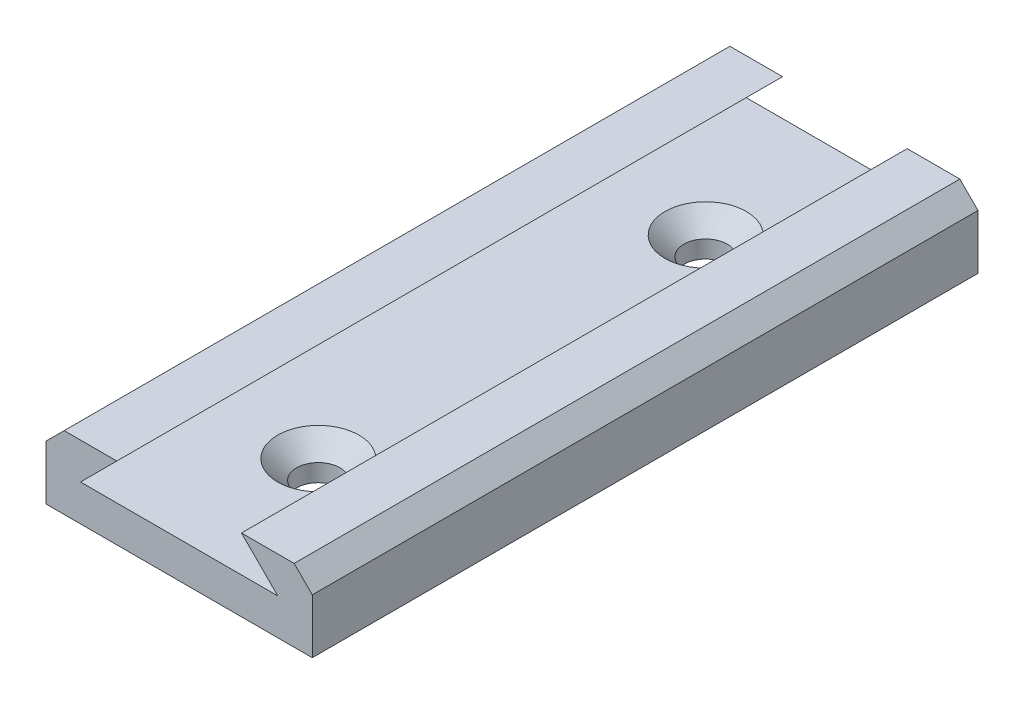
SolidWorks part; units mm, degrees
ref_plane "Front Plane" through (0, 0, 0) normal (0, 0, 1) x (1, 0, 0)
ref_plane "Top Plane" through (0, 0, 0) normal (0, 1, 0) x (1, 0, 0)
ref_plane "Right Plane" through (0, 0, 0) normal (1, 0, 0) x (0, 0, -1)
sketch "Sketch2" plane through (0, 0, 0) normal (0, 0, 1) x (1, 0, 0)
  line L0 (-11, 0) -> (11, 0)
  line L1 (11, 0) -> (11, 4.5)
  line L2 (11, 4.5) -> (9.5, 6)
  line L3 (9.5, 6) -> (5.15, 6)
  line L4 (5.15, 6) -> (8.15, 3)
  line L5 (8.15, 3) -> (-8.15, 3)
  line L6 (-8.15, 3) -> (-5.15, 6)
  line L7 (-5.15, 6) -> (-9.5, 6)
  line L8 (-9.5, 6) -> (-11, 4.5)
  line L9 (-11, 4.5) -> (-11, 0)
  point P0 (0, 0)
  point P12 (0, 3)
  dimension "D1" = 16.3
  dimension "D2" = 45
  dimension "D3" = 3
  dimension "D4" = 45
  dimension "D5" = 22
  dimension "D6" = 1.5
  dimension "D7" = 1.5
  dimension "D8" = 3
extrude "Boss-Extrude1" add sketch "Sketch2" along normal blind 55
sketch "Sketch5" plane through (0, 3, 0) normal (0, 1, 0) x (1, 0, 0)
  line L0 (-11, -27.5) -> (11, -27.5) construction
  line L1 (-11, -55) -> (-11, 0) construction
  line L2 (11, -55) -> (11, 0) construction
  point P0 (0, -11.5)
  point P2 (0, -43.5)
  point P13 (0, 0)
  dimension "D1" = 32
hole_wizard "CSK for M3 Hex Socket Countersunk Cap Screw1" positions "Sketch5" profile "Sketch4" countersink size "M3" standard "ISO" end condition through all
sketch "Sketch4" plane through (0, 3, 11.5) normal (1, 0, 0) x (0, 0, 1)
  line L0 (0, 0) -> (0, 3)
  line L1 (0, 3) -> (1.8, 3)
  line L2 (1.8, 3) -> (1.8, 1.56)
  line L3 (1.8, 1.56) -> (3.36, 0)
  line L5 (3.36, 0) -> (0, 0)
  line L6 (-1.8, 1.56) -> (-3.36, 0) construction
  line L11 (0, -6.35) -> (0, 107.95) construction
  dimension "Thru Hole Dia." = 3.6
  dimension "Thru Hole Depth" = 3
  dimension "Near C'Sink Dia." = 6.72
  dimension "Near C'Sink Angle" = 90
